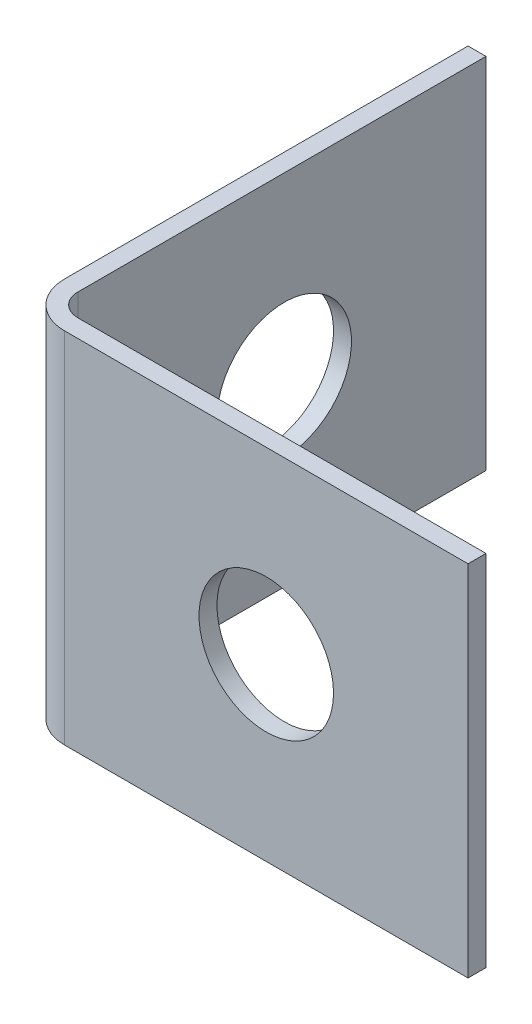
SolidWorks part; units mm, degrees
material "AISI 1020"
ref_plane "Front Plane" through (0, 0, 0) normal (0, 0, 1) x (1, 0, 0)
ref_plane "Top Plane" through (0, 0, 0) normal (0, 1, 0) x (1, 0, 0)
ref_plane "Right Plane" through (0, 0, 0) normal (1, 0, 0) x (0, 0, -1)
sketch "Sketch1" plane through (0, 0, 0) normal (0, 1, 0) x (1, 0, 0)
  line L0 (1.27, 30.48) -> (30.48, 30.48)
  line L1 (0, 0) -> (31.75, 0)
  line L2 (0, 0) -> (0, 31.75)
  line L3 (0, 31.75) -> (31.75, 31.75)
  line L4 (31.75, 0) -> (31.75, 31.75)
  line L5 (30.48, 1.27) -> (30.48, 30.48)
  line L6 (1.27, 1.27) -> (30.48, 1.27)
  line L7 (1.27, 1.27) -> (1.27, 30.48)
  line L8 (1.27, 30.48) -> (1.27, 31.75)
  line L9 (30.48, 1.27) -> (31.75, 1.27)
  dimension "D1" = 31.75
  dimension "D2" = 31.75
  dimension "D3" = 1.27
extrude "Boss-Extrude1" add sketch "Sketch1" along normal blind 1219.2 contours L9 L6 L7 L8 L3 L2 L1 L4
sketch "Sketch3" plane through (0, 0, 0) normal (-1, 0, 0) x (0, 0, 1)
  line L0 (-17.4625, 0) -> (-17.4625, 12.7) construction
  line L2 (-31.75, 1219.2) -> (-31.75, 0) construction
  circle A0 centre (-17.4625, 12.7) radius 4.7625
  circle A1 centre (-17.4625, 38.1) radius 4.7625
  circle A2 centre (-17.4625, 63.5) radius 4.7625
  circle A3 centre (-17.4625, 88.9) radius 4.7625
  circle A4 centre (-17.4625, 114.3) radius 4.7625
  circle A5 centre (-17.4625, 139.7) radius 4.7625
  circle A6 centre (-17.4625, 165.1) radius 4.7625
  circle A7 centre (-17.4625, 190.5) radius 4.7625
  circle A8 centre (-17.4625, 215.9) radius 4.7625
  circle A9 centre (-17.4625, 241.3) radius 4.7625
  circle A10 centre (-17.4625, 266.7) radius 4.7625
  circle A11 centre (-17.4625, 292.1) radius 4.7625
  circle A12 centre (-17.4625, 317.5) radius 4.7625
  circle A13 centre (-17.4625, 342.9) radius 4.7625
  circle A14 centre (-17.4625, 368.3) radius 4.7625
  circle A15 centre (-17.4625, 393.7) radius 4.7625
  circle A16 centre (-17.4625, 419.1) radius 4.7625
  circle A17 centre (-17.4625, 444.5) radius 4.7625
  circle A18 centre (-17.4625, 469.9) radius 4.7625
  circle A19 centre (-17.4625, 495.3) radius 4.7625
  circle A20 centre (-17.4625, 520.7) radius 4.7625
  circle A21 centre (-17.4625, 546.1) radius 4.7625
  circle A22 centre (-17.4625, 571.5) radius 4.7625
  circle A23 centre (-17.4625, 596.9) radius 4.7625
  circle A24 centre (-17.4625, 622.3) radius 4.7625
  circle A25 centre (-17.4625, 647.7) radius 4.7625
  circle A26 centre (-17.4625, 673.1) radius 4.7625
  circle A27 centre (-17.4625, 698.5) radius 4.7625
  circle A28 centre (-17.4625, 723.9) radius 4.7625
  circle A29 centre (-17.4625, 749.3) radius 4.7625
  circle A30 centre (-17.4625, 774.7) radius 4.7625
  circle A31 centre (-17.4625, 800.1) radius 4.7625
  circle A32 centre (-17.4625, 825.5) radius 4.7625
  circle A33 centre (-17.4625, 850.9) radius 4.7625
  circle A34 centre (-17.4625, 876.3) radius 4.7625
  circle A35 centre (-17.4625, 901.7) radius 4.7625
  circle A36 centre (-17.4625, 927.1) radius 4.7625
  circle A37 centre (-17.4625, 952.5) radius 4.7625
  circle A38 centre (-17.4625, 977.9) radius 4.7625
  circle A39 centre (-17.4625, 1003.3) radius 4.7625
  circle A40 centre (-17.4625, 1028.7) radius 4.7625
  circle A41 centre (-17.4625, 1054.1) radius 4.7625
  circle A42 centre (-17.4625, 1079.5) radius 4.7625
  circle A43 centre (-17.4625, 1104.9) radius 4.7625
  circle A44 centre (-17.4625, 1130.3) radius 4.7625
  circle A45 centre (-17.4625, 1155.7) radius 4.7625
  circle A46 centre (-17.4625, 1181.1) radius 4.7625
  circle A47 centre (-17.4625, 1206.5) radius 4.7625
  dimension "D1" = 9.525
  dimension "D2" = 12.7
  dimension "D4" = 14.2875
  dimension "D3" = 48
extrude "Cut-Extrude1" cut sketch "Sketch3" against normal up to next (1.27 mm away)
sketch "Sketch4" plane through (0, 0, 0) normal (0, 0, 1) x (1, 0, 0)
  line L0 (17.4625, 1219.2) -> (17.4625, 1206.5) construction
  line L2 (31.75, 1219.2) -> (31.75, 0) construction
  circle A0 centre (17.4625, 1206.5) radius 4.7625
  circle A1 centre (17.4625, 1181.1) radius 4.7625
  circle A2 centre (17.4625, 1155.7) radius 4.7625
  circle A3 centre (17.4625, 1130.3) radius 4.7625
  circle A4 centre (17.4625, 1104.9) radius 4.7625
  circle A5 centre (17.4625, 1079.5) radius 4.7625
  circle A6 centre (17.4625, 1054.1) radius 4.7625
  circle A7 centre (17.4625, 1028.7) radius 4.7625
  circle A8 centre (17.4625, 1003.3) radius 4.7625
  circle A9 centre (17.4625, 977.9) radius 4.7625
  circle A10 centre (17.4625, 952.5) radius 4.7625
  circle A11 centre (17.4625, 927.1) radius 4.7625
  circle A12 centre (17.4625, 901.7) radius 4.7625
  circle A13 centre (17.4625, 876.3) radius 4.7625
  circle A14 centre (17.4625, 850.9) radius 4.7625
  circle A15 centre (17.4625, 825.5) radius 4.7625
  circle A16 centre (17.4625, 800.1) radius 4.7625
  circle A17 centre (17.4625, 774.7) radius 4.7625
  circle A18 centre (17.4625, 749.3) radius 4.7625
  circle A19 centre (17.4625, 723.9) radius 4.7625
  circle A20 centre (17.4625, 698.5) radius 4.7625
  circle A21 centre (17.4625, 673.1) radius 4.7625
  circle A22 centre (17.4625, 647.7) radius 4.7625
  circle A23 centre (17.4625, 622.3) radius 4.7625
  circle A24 centre (17.4625, 596.9) radius 4.7625
  circle A25 centre (17.4625, 571.5) radius 4.7625
  circle A26 centre (17.4625, 546.1) radius 4.7625
  circle A27 centre (17.4625, 520.7) radius 4.7625
  circle A28 centre (17.4625, 495.3) radius 4.7625
  circle A29 centre (17.4625, 469.9) radius 4.7625
  circle A30 centre (17.4625, 444.5) radius 4.7625
  circle A31 centre (17.4625, 419.1) radius 4.7625
  circle A32 centre (17.4625, 393.7) radius 4.7625
  circle A33 centre (17.4625, 368.3) radius 4.7625
  circle A34 centre (17.4625, 342.9) radius 4.7625
  circle A35 centre (17.4625, 317.5) radius 4.7625
  circle A36 centre (17.4625, 292.1) radius 4.7625
  circle A37 centre (17.4625, 266.7) radius 4.7625
  circle A38 centre (17.4625, 241.3) radius 4.7625
  circle A39 centre (17.4625, 215.9) radius 4.7625
  circle A40 centre (17.4625, 190.5) radius 4.7625
  circle A41 centre (17.4625, 165.1) radius 4.7625
  circle A42 centre (17.4625, 139.7) radius 4.7625
  circle A43 centre (17.4625, 114.3) radius 4.7625
  circle A44 centre (17.4625, 88.9) radius 4.7625
  circle A45 centre (17.4625, 63.5) radius 4.7625
  circle A46 centre (17.4625, 38.1) radius 4.7625
  circle A47 centre (17.4625, 12.7) radius 4.7625
  dimension "D1" = 9.525
  dimension "D2" = 12.7
  dimension "D4" = 14.2875
  dimension "D3" = 48
extrude "Cut-Extrude2" cut sketch "Sketch4" against normal up to next (1.27 mm away)
fillet "Fillet1" radius 3.175 1 edges at (0, 609.6, 0)
fillet "Fillet2" radius 1.5875 1 edges at (1.27, 609.6, -1.27)
sketch "Sketch5" plane through (0, 1219.2, 0) normal (0, 1, 0) x (1, 0, 0)
  line L12 (0, 31.75) -> (0, 3.175)
  line L13 (3.175, 0) -> (31.75, 0)
  line L14 (31.75, 0) -> (31.75, 1.27)
  line L15 (31.75, 1.27) -> (2.8575, 1.27)
  line L16 (1.27, 2.8575) -> (1.27, 31.75)
  line L17 (1.27, 31.75) -> (0, 31.75)
  line L18 (0, 31.75) -> (0, 3.175)
  line L19 (3.175, 0) -> (31.75, 0)
  line L20 (31.75, 0) -> (31.75, 1.27)
  line L21 (31.75, 1.27) -> (2.8575, 1.27)
  line L22 (1.27, 2.8575) -> (1.27, 31.75)
  line L23 (1.27, 31.75) -> (0, 31.75)
  arc A4 (0, 3.175) -> (3.175, 0) centre (3.175, 3.175) ccw
  arc A5 (1.27, 2.8575) -> (2.8575, 1.27) centre (2.8575, 2.8575) ccw
  arc A6 (0, 3.175) -> (3.175, 0) centre (3.175, 3.175) ccw
  arc A7 (1.27, 2.8575) -> (2.8575, 1.27) centre (2.8575, 2.8575) ccw
  dimension "D1" = 0
extrude "Cut-Extrude3" cut sketch "Sketch5" against normal blind 1193.8
